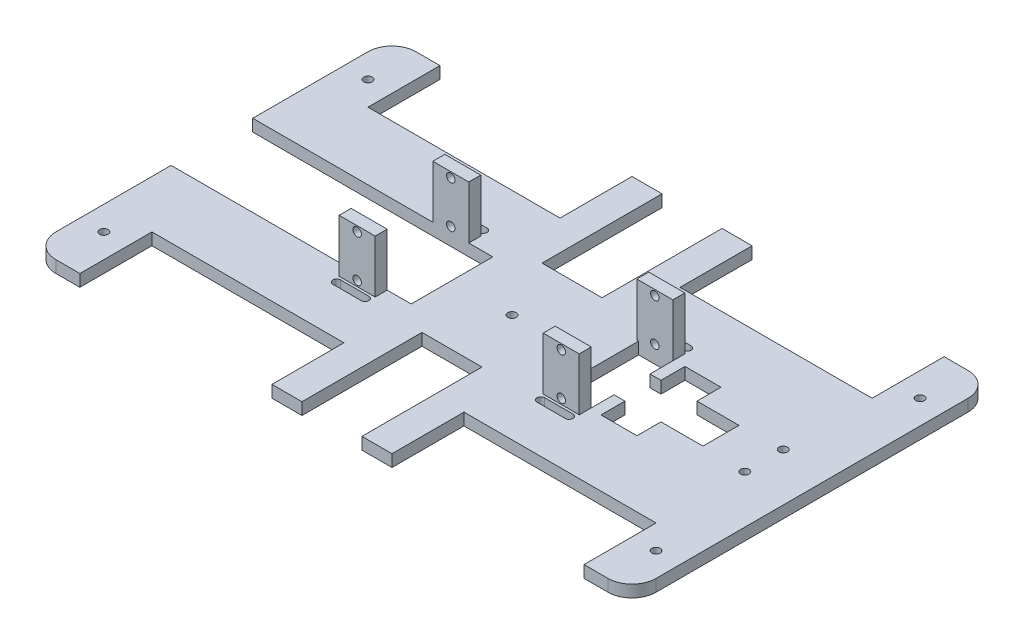
SolidWorks part; units mm, degrees
ref_plane "前视基准面" through (0, 0, 0) normal (0, 0, 1) x (1, 0, 0)
ref_plane "上视基准面" through (0, 0, 0) normal (0, 1, 0) x (1, 0, 0)
ref_plane "右视基准面" through (0, 0, 0) normal (1, 0, 0) x (0, 0, -1)
other "Configuration Table"
sketch "草图1" plane through (0, 0, 0) normal (0, 1, 0) x (1, 0, 0)
  line L1 (125, -75) -> (-125, -75)
  line L2 (125, -75) -> (125, 75)
  line L3 (125, 75) -> (-125, 75)
  line L4 (-125, -75) -> (-125, 75)
  line L5 (125, -75) -> (-125, 75) construction
  line L6 (125, 75) -> (-125, -75) construction
  point P0 (0, 0)
  dimension "D1" = 250
  dimension "D2" = 150
extrude "凸台-拉伸1" add sketch "草图1" along normal blind 5
ref_plane "基准面1" through (0, 0, 22) normal (0, 0, 1) x (1, 0, 0)
sketch "草图2" plane through (0, 0, 22) normal (0, 0, 1) x (1, 0, 0)
  line L0 (-125, 5) -> (125, 5) construction
  line L1 (-35, 27) -> (-50, 27)
  line L2 (-35, 27) -> (-35, 5)
  line L3 (-35, 5) -> (-50, 5)
  line L4 (-50, 27) -> (-50, 5)
  line L5 (-35, 27) -> (-50, 5) construction
  line L6 (-35, 5) -> (-50, 27) construction
  point P0 (-42.5, 16)
  dimension "D1" = 22
  dimension "D2" = 15
  dimension "D3" = 35
sketch "草图3" plane through (0, 5, 0) normal (0, 1, 0) x (1, 0, 0)
  line L0 (-125, 0) -> (125, 0) construction
  line L1 (-125, 75) -> (-125, -75) construction
  line L2 (125, -75) -> (125, 75) construction
  line L3 (0, 75) -> (0, -75) construction
  line L4 (125, 75) -> (-125, 75) construction
  line L5 (-125, -75) -> (125, -75) construction
extrude "凸台-拉伸2" add sketch "草图2" against normal blind 5 contours L2 L3 L4 L1
mirror "镜向1" about plane through (0, 0, 0) normal (0, 0, 1) of "凸台-拉伸2"
mirror "镜向2" about plane through (0, 0, 0) normal (1, 0, 0) of "凸台-拉伸2", "镜向1"
sketch "草图7" plane through (0, 5, 0) normal (0, 1, 0) x (1, 0, 0)
  line L1 (-125, -75) -> (125, -75) construction
  line L2 (-125, 75) -> (-125, -75) construction
  circle A0 centre (-115, -55) radius 1.75
  dimension "D1" = 3.5
  dimension "D2" = 20
  dimension "D3" = 10
extrude "切除-拉伸1" cut sketch "草图7" against normal through all both and the other way through all
mirror "镜向3" about plane through (0, 0, 0) normal (0, 0, 1) of "切除-拉伸1"
mirror "镜向4" about plane through (0, 0, 0) normal (1, 0, 0) of "镜向3", "切除-拉伸1"
fillet "圆角1" radius 10 4 edges at (125, 2.5, 75) (-125, 2.5, 75) (-125, 2.5, -75) (125, 2.5, -75)
sketch "草图12" plane through (125, 0, 0) normal (1, 0, 0) x (0, 0, -1)
  line L0 (75, 5) -> (-75, 5) construction
  line L1 (15, 16) -> (-15, 16)
  line L2 (15, 16) -> (15, 5)
  line L3 (15, 5) -> (-15, 5)
  line L4 (-15, 16) -> (-15, 5)
  line L5 (15, 16) -> (-15, 5) construction
  line L6 (15, 5) -> (-15, 16) construction
  point P0 (0, 10.5)
  dimension "D1" = 11
  dimension "D2" = 30
  dimension "D3" = 15
extrude "凸台-拉伸4" add sketch "草图12" against normal blind 3
sketch "草图13" plane through (125, 0, 0) normal (1, 0, 0) x (0, 0, -1)
  line L0 (-15, 16) -> (-15, 5) construction
  line L1 (15, 16) -> (-15, 16)
  line L2 (15, 16) -> (15, 13)
  line L3 (15, 13) -> (-15, 13)
  line L4 (-15, 16) -> (-15, 13)
  line L5 (15, 16) -> (-15, 13) construction
  line L6 (15, 13) -> (-15, 16) construction
  line L7 (75, 5) -> (-75, 5) construction
  point P0 (0, 14.5)
  dimension "D1" = 30
  dimension "D2" = 3
  dimension "D3" = 8
extrude "凸台-拉伸5" add sketch "草图13" along normal blind 50
sketch "草图15" plane through (0, 16, 0) normal (0, 1, 0) x (1, 0, 0)
  line L0 (165, 15) -> (165, -15)
  line L1 (122, 15) -> (175, 15) construction
  line L2 (122, -15) -> (175, -15) construction
  line L3 (175, 15) -> (175, -15) construction
  dimension "D1" = 10
extrude "切除-拉伸4" cut sketch "草图15" against normal through all both and the other way through all
sketch "草图16" plane through (0, 16, 0) normal (0, 1, 0) x (1, 0, 0)
  line L0 (122, 15) -> (122, -15) construction
  line L1 (165, -8) -> (122, -8)
  line L2 (165, -8) -> (165, 8)
  line L3 (165, 8) -> (122, 8)
  line L4 (122, -8) -> (122, 8)
  line L5 (165, -8) -> (122, 8) construction
  line L6 (165, 8) -> (122, -8) construction
  line L7 (122, 15) -> (165, 15) construction
  line L8 (122, -15) -> (165, -15) construction
  line L9 (165, -15) -> (165, 15) construction
  line L11 (128, -10) -> (122, -10)
  line L12 (128, -10) -> (128, 10)
  line L13 (128, 10) -> (122, 10)
  line L14 (122, -10) -> (122, 10)
  line L15 (128, -10) -> (122, 10) construction
  line L16 (128, 10) -> (122, -10) construction
  circle A0 centre (135, 8) radius 1.75
  circle A1 centre (155, 8) radius 1.75
  point P0 (143.5, 0)
  point P17 (125, 0)
  dimension "D5" = 3.5
  dimension "D6" = 3.5
  dimension "D1" = 43
  dimension "D2" = 0
  dimension "D3" = 7
  dimension "D4" = 7
  dimension "D7" = 10
  dimension "D8" = 30
extrude "切除-拉伸5" cut sketch "草图16" against normal through all both and the other way through all contours A0 | A1
mirror "镜向7" about plane through (0, 0, 0) normal (0, 0, 1) of "切除-拉伸5"
sketch "草图19" plane through (0, 16, 0) normal (0, 1, 0) x (1, 0, 0)
  line L1 (122, -10) -> (128, -10)
  line L2 (122, -10) -> (122, 10)
  line L3 (122, 10) -> (128, 10)
  line L4 (128, -10) -> (128, 10)
  line L5 (122, -10) -> (128, 10) construction
  line L6 (122, 10) -> (128, -10) construction
  point P0 (125, 0)
  dimension "D1" = 6
  dimension "D2" = 20
extrude "切除-拉伸6" cut sketch "草图19" against normal blind 5 and the other way through all
sketch "草图20" plane through (0, 5, 0) normal (0, 1, 0) x (1, 0, 0)
  line L0 (0, 75) -> (0, -75) construction
  line L1 (-15, -25) -> (15, -25)
  line L2 (-15, -25) -> (-15, -75)
  line L3 (-15, -75) -> (15, -75)
  line L4 (15, -25) -> (15, -75)
  line L5 (-15, -25) -> (15, -75) construction
  line L6 (-15, -75) -> (15, -25) construction
  line L7 (-115, -75) -> (115, -75) construction
  point P0 (0, -50)
  dimension "D1" = 30
  dimension "D2" = 50
sketch "草图21" plane through (0, 5, 0) normal (0, 1, 0) x (1, 0, 0)
  line L0 (-35, -17) -> (-35, -22) construction
  line L1 (35, -17) -> (35, -22) construction
  line L2 (0, 75) -> (0, -75) construction
  line L3 (105, -45) -> (-105, -45)
  line L4 (105, -45) -> (105, -75)
  line L5 (105, -75) -> (-105, -75)
  line L6 (-105, -45) -> (-105, -75)
  line L7 (105, -45) -> (-105, -75) construction
  line L8 (105, -75) -> (-105, -45) construction
  line L9 (-115, -75) -> (115, -75) construction
  point P4 (0, -60)
  dimension "D1" = 70
  dimension "D2" = 210
  dimension "D3" = 30
extrude "切除-拉伸8" cut sketch "草图21" against normal blind 5
sketch "草图23" plane through (0, 5, 0) normal (0, 1, 0) x (1, 0, 0)
  line L0 (-105, -45) -> (-105, -75) construction
  line L1 (-50, -17) -> (-50, -22) construction
  line L2 (0, 75) -> (0, -75) construction
  line L3 (25, -75) -> (-25, -75)
  line L4 (25, -75) -> (25, -45)
  line L5 (25, -45) -> (-25, -45)
  line L6 (-25, -75) -> (-25, -45)
  line L7 (25, -75) -> (-25, -45) construction
  line L8 (25, -45) -> (-25, -75) construction
  line L9 (105, -45) -> (-105, -45) construction
  line L10 (-35, -17) -> (-35, -22) construction
  line L11 (35, -17) -> (35, -22) construction
  point P4 (0, -60)
  dimension "D1" = 55
  dimension "D2" = 30
  dimension "D3" = 50
  dimension "D4" = 70
  dimension "D5" = 80
extrude "凸台-拉伸6" add sketch "草图23" against normal blind 5
mirror "镜向10" about plane through (0, 0, 0) normal (0, 0, 1) of "凸台-拉伸6", "切除-拉伸8"
sketch "草图24" plane through (0, 5, 0) normal (0, 1, 0) x (1, 0, 0)
  line L0 (0, 75) -> (0, -75) construction
  line L1 (12.5, 25) -> (-12.5, 25)
  line L2 (12.5, 25) -> (12.5, 75)
  line L3 (12.5, 75) -> (-12.5, 75)
  line L4 (-12.5, 25) -> (-12.5, 75)
  line L5 (12.5, 25) -> (-12.5, 75) construction
  line L6 (12.5, 75) -> (-12.5, 25) construction
  line L7 (-25, 75) -> (25, 75) construction
  point P0 (0, 50)
  dimension "D1" = 25
  dimension "D2" = 50
extrude "切除-拉伸9" cut sketch "草图24" against normal blind 5
mirror "镜向11" about plane through (0, 0, 0) normal (0, 0, 1) of "切除-拉伸9"
sketch "草图25" plane through (0, 5, 0) normal (0, 1, 0) x (1, 0, 0)
  line L0 (-125, 0) -> (125, 0) construction
  line L1 (-25, -17) -> (-125, -17)
  line L2 (-25, -17) -> (-25, 17)
  line L3 (-25, 17) -> (-125, 17)
  line L4 (-125, -17) -> (-125, 17)
  line L5 (-25, -17) -> (-125, 17) construction
  line L6 (-25, 17) -> (-125, -17) construction
  line L7 (-125, 65) -> (-125, -65) construction
  line L8 (-35, -17) -> (-50, -17) construction
  point P0 (-75, 0)
  dimension "D1" = 34
  dimension "D2" = 100
  dimension "D3" = 0
extrude "切除-拉伸10" cut sketch "草图25" against normal blind 5
sketch "草图26" plane through (0, 5, 0) normal (0, 1, 0) x (1, 0, 0)
  line L0 (-125, 0) -> (125, 0) construction
  line L1 (87.0543, -7.5) -> (37.0543, -7.5)
  line L2 (87.0543, -7.5) -> (87.0543, 7.5)
  line L3 (87.0543, 7.5) -> (37.0543, 7.5)
  line L4 (37.0543, -7.5) -> (37.0543, 7.5)
  line L5 (87.0543, -7.5) -> (37.0543, 7.5) construction
  line L6 (87.0543, 7.5) -> (37.0543, -7.5) construction
  line L8 (69.5543, -17.5) -> (54.5543, -17.5)
  line L9 (69.5543, -17.5) -> (69.5543, 17.5)
  line L10 (69.5543, 17.5) -> (54.5543, 17.5)
  line L11 (54.5543, -17.5) -> (54.5543, 17.5)
  line L12 (69.5543, -17.5) -> (54.5543, 17.5) construction
  line L13 (69.5543, 17.5) -> (54.5543, -17.5) construction
  point P0 (62.0543, 0)
  point P7 (62.0543, 0)
  dimension "D1" = 15
  dimension "D2" = 35
  dimension "D3" = 15
  dimension "D4" = 50
extrude "切除-拉伸11" cut sketch "草图26" against normal blind 5 contours L10 L11 L8 L9 | L2 L3 L4 L1
sketch "草图27" plane through (0, 5, 0) normal (0, 1, 0) x (1, 0, 0)
  circle A0 centre (0, 0) radius 1.75
  dimension "D1" = 3.5
extrude "切除-拉伸12" cut sketch "草图27" against normal blind 5
sketch "草图29" plane through (0, 0, 22) normal (0, 0, 1) x (1, 0, 0)
  line L0 (-42.5, 27) -> (-42.5, 5) construction
  line L1 (-35, 27) -> (-50, 27) construction
  line L2 (-125, 5) -> (125, 5) construction
  circle A0 centre (-42.5, 24.75) radius 1.75
  circle A1 centre (-42.5, 7.25) radius 1.75
  dimension "D1" = 3.5
  dimension "D2" = 3.5
  dimension "D3" = 2.25
  dimension "D4" = 2.25
extrude "切除-拉伸13" cut sketch "草图29" against normal blind 5
mirror "镜向12" about plane through (0, 0, 0) normal (1, 0, 0) of "切除-拉伸13" second plane through (0, 0, 0) second plane normal (0, 0, 1)
sketch "草图32" plane through (0, 5, 0) normal (0, 1, 0) x (1, 0, 0)
  line L0 (-48.4, 24.6) -> (-36.6, 24.6) construction
  line L1 (-48.4, 26.2) -> (-36.6, 26.2)
  line L2 (-48.4, 23) -> (-36.6, 23)
  line L3 (-35, 22) -> (-50, 22) construction
  line L4 (-50, 17) -> (-50, 22) construction
  arc A0 (-48.4, 26.2) -> (-48.4, 23) centre (-48.4, 24.6) ccw
  arc A1 (-36.6, 23) -> (-36.6, 26.2) centre (-36.6, 24.6) ccw
  point P2 (-42.5, 24.6)
  dimension "D2" = 1.6
  dimension "D1" = 11.8
  dimension "D3" = 1
  dimension "D4" = 1.6
extrude "切除-拉伸14" cut sketch "草图32" against normal blind 5
mirror "镜向13" about plane through (0, 0, 0) normal (1, 0, 0) of "切除-拉伸14" second plane through (0, 0, 0) second plane normal (0, 0, 1)
sketch "草图33" plane through (0, 5, 0) normal (0, 1, 0) x (1, 0, 0)
  line L0 (-125, 0) -> (125, 0) construction
  line L1 (50, -17) -> (35.7663, -17)
  line L2 (50, -17) -> (50, 17)
  line L3 (50, 17) -> (35.7663, 17)
  line L4 (35.7663, -17) -> (35.7663, 17)
  line L5 (50, -17) -> (35.7663, 17) construction
  line L6 (50, 17) -> (35.7663, -17) construction
  line L7 (35, 17) -> (50, 17) construction
  line L8 (50, 17) -> (50, 22) construction
  line L9 (35, 17) -> (35.7663, 17)
  line L10 (35, 17) -> (35, -17)
  line L11 (35.7663, -17) -> (35, -17)
  point P0 (42.8832, 0)
  dimension "D1" = 34
  dimension "D2" = 0
extrude "切除-拉伸15" cut sketch "草图33" against normal blind 5 contours L2 L1 L4 L3
sketch "草图34" plane through (0, 5, 0) normal (0, 1, 0) x (1, 0, 0)
  line L0 (-125, 0) -> (125, 0) construction
  line L5 (124.2446, -15.0703) -> (103.3529, 15.0703) construction
  line L6 (124.2446, 15.0703) -> (103.3529, -15.0703) construction
  line L7 (135, 8) -> (93.6192, 8) construction
  line L8 (135, -8) -> (93.6192, -8) construction
  line L9 (125, 10) -> (125, -10) construction
  circle A1 centre (105, 8) radius 1.75
  circle A2 centre (105, -8) radius 1.75
  point P0 (113.7987, 0)
  dimension "D1" = 3.5
  dimension "D2" = 3.5
  dimension "D3" = 20
extrude "切除-拉伸16" cut sketch "草图34" against normal blind 10
sketch "草图35" plane through (122, 0, 0) normal (-1, 0, 0) x (0, 0, 1)
  line L1 (15, 5) -> (-15, 5)
  line L2 (15, 5) -> (15, 16)
  line L3 (15, 16) -> (-15, 16)
  line L4 (-15, 5) -> (-15, 16)
extrude "切除-拉伸17" cut sketch "草图35" against normal blind 65
ref_plane "基准面3" through (-36.6, 5, -26.2) normal (-1, 0, 0) x (0, 0, 1)
